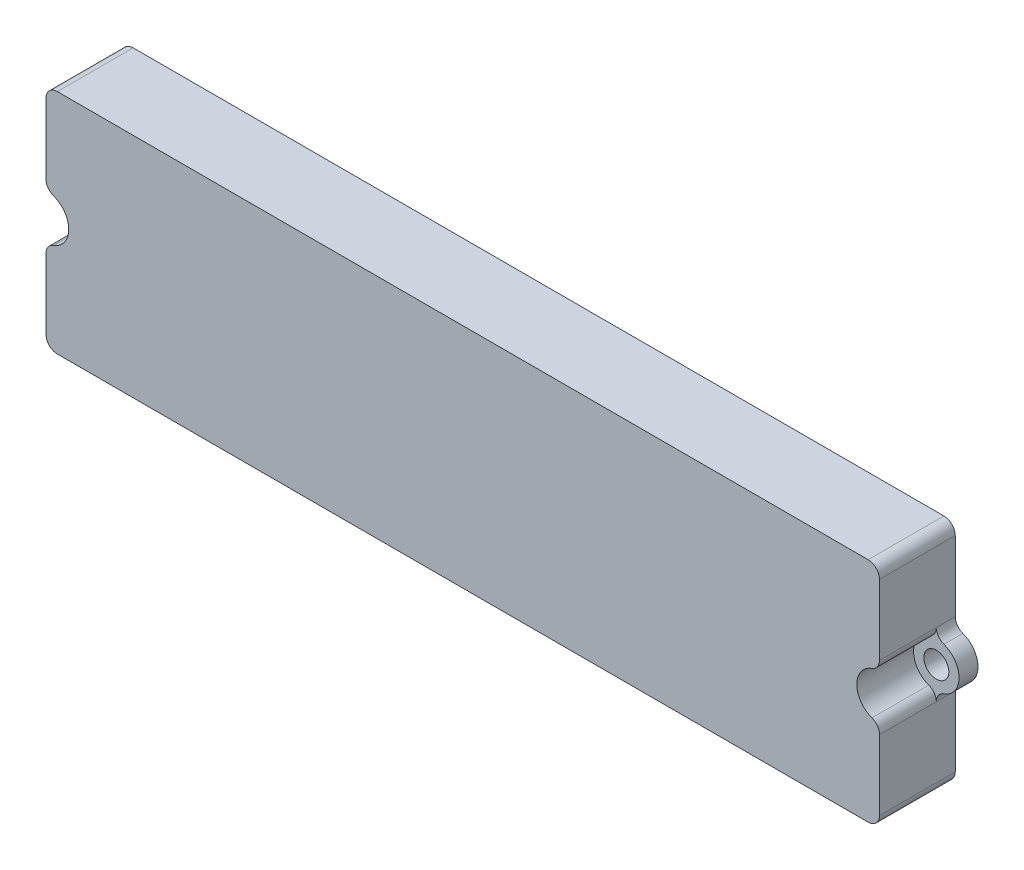
SolidWorks part; units mm, degrees
ref_plane "Front Plane" through (0, 0, 0) normal (0, 0, 1) x (1, 0, 0)
ref_plane "Top Plane" through (0, 0, 0) normal (0, 1, 0) x (1, 0, 0)
ref_plane "Right Plane" through (0, 0, 0) normal (1, 0, 0) x (0, 0, -1)
sketch "Sketch1" plane through (0, 0, 0) normal (0, 0, 1) x (1, 0, 0)
  line L1 (-110, -30) -> (110, -30)
  line L2 (-110, -30) -> (-110, 30)
  line L3 (-110, 30) -> (110, 30)
  line L4 (110, -30) -> (110, 30)
  line L5 (-110, -30) -> (110, 30) construction
  line L6 (-110, 30) -> (110, -30) construction
  point P0 (0, 0)
  dimension "D1" = 60
  dimension "D2" = 220
extrude "Boss-Extrude1" add sketch "Sketch1" along normal blind 20
fillet "Fillet1" radius 3 4 edges at (-110, -30, 10) (110, -30, 10) (110, 30, 10) (-110, 30, 10)
sketch "Sketch2" plane through (0, 0, 20) normal (0, 0, 1) x (1, 0, 0)
  line L0 (-110, 27) -> (-110, -27) construction
  line L1 (110, -27) -> (110, 27) construction
  circle A0 centre (-110, 0) radius 6
  circle A1 centre (110, 0) radius 6
  dimension "D1" = 12
  dimension "D2" = 12
extrude "Boss-Extrude2" add sketch "Sketch2" against normal up to surface (20 mm away) up to face at (0, 0, 0)
sketch "Sketch3" plane through (0, 0, 20) normal (0, 0, 1) x (1, 0, 0)
  circle A0 centre (-110, 0) radius 3.3
  circle A1 centre (110, 0) radius 3.3
  dimension "D1" = 6.6
  dimension "D2" = 6.6
extrude "Cut-Extrude1" cut sketch "Sketch3" against normal blind 20
sketch "Sketch4" plane through (0, 0, 20) normal (0, 0, 1) x (1, 0, 0)
  circle A0 centre (-110, 0) radius 6
  circle A1 centre (110, 0) radius 6
  dimension "D1" = 12
  dimension "D2" = 12
extrude "Cut-Extrude2" cut sketch "Sketch4" against normal blind 15
fillet "Fillet2" radius 3 2 edges at (-110, -6, 2.5) (-110, 6, 2.5)
fillet "Fillet3" radius 3 1 edges at (-110, 6, 12.5)
fillet "Fillet4" radius 3 1 edges at (-110, -6, 12.5)
fillet "Fillet6" radius 3 2 edges at (110, 6, 2.5) (110, -6, 2.5)
fillet "Fillet7" radius 3 2 edges at (110, 6, 12.5) (110, -6, 12.5)
